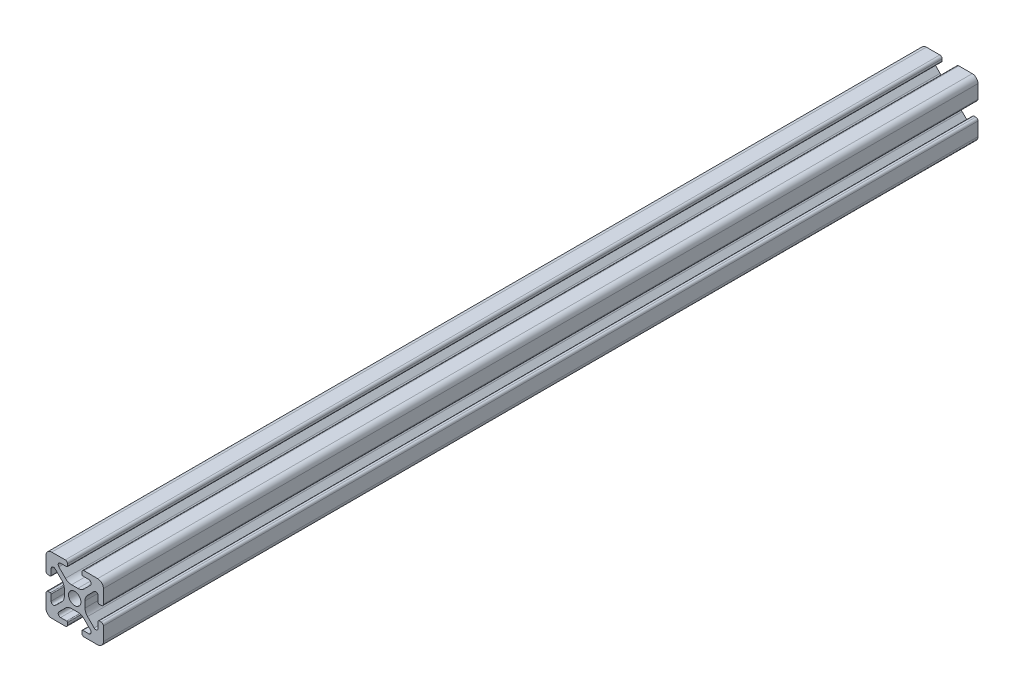
SolidWorks part; units mm, degrees
ref_plane "Front Plane" through (0, 0, 0) normal (0, 0, 1) x (1, 0, 0)
ref_plane "Top Plane" through (0, 0, 0) normal (0, 1, 0) x (1, 0, 0)
ref_plane "Right Plane" through (0, 0, 0) normal (1, 0, 0) x (0, 0, -1)
sketch "Sketch1" plane through (0, 0, 0) normal (0, 0, 1) x (1, 0, 0)
  line L0 (0, 10) -> (0, -10) construction
  line L1 (10, 0) -> (-10, 0) construction
  line L2 (-2.5, 10) -> (2.5, 10) construction
  line L3 (-5.75, 8.2) -> (5.75, 8.2) construction
  circle A0 centre (0, 0) radius 2.15 construction
  point P4 (0, 0)
  point P8 (0, 0)
  point P10 (0, 3.6)
  point P14 (0, 10)
  point P17 (0, 8.2)
  dimension "Thru Hole" = 4.3
  dimension "Height" = 20
  dimension "T Slot Depth" = 6.4
  dimension "T Slot Top Width" = 5
  dimension "T Slot Max Width" = 11.5
  dimension "Wall" = 1.8
sketch "Sketch2" plane through (0, 0, 0) normal (1, 0, 0) x (0, 0, -1)
  line L0 (152.4, 0) -> (-152.4, 0) construction
  point P4 (0, 0)
  dimension "D1" = 304.8
sketch "Sketch3" plane through (0, 0, 0) normal (0, 0, 1) x (1, 0, 0)
  line L0 (3.2874, 10) -> (8, 10)
  line L1 (10, 8) -> (10, -8) construction
  line L2 (8, -10) -> (-8, -10) construction
  line L3 (-10, 10) -> (10, -10) construction
  line L4 (2.5, 9.2126) -> (2.5, 8.5048)
  line L5 (-5.75, 8.2) -> (5.75, 8.2) construction
  line L6 (2.8048, 8.2) -> (4.9118, 8.2)
  line L7 (5.5045, 6.7691) -> (3.2141, 4.4787)
  line L8 (1.0928, 3.6) -> (-1.0928, 3.6)
  line L9 (0, 10) -> (0, -10) construction
  line L10 (5.75, 8.2) -> (5.75, 0) construction
  line L11 (10, 0) -> (-10, 0) construction
  line L12 (0, 0) -> (0, 10) construction
  line L13 (-2.5, 9.2126) -> (-2.5, 8.5048)
  line L14 (-5.5045, 6.7691) -> (-3.2141, 4.4787)
  line L15 (-2.8048, 8.2) -> (-4.9118, 8.2)
  line L16 (-3.2874, 10) -> (-8, 10)
  line L17 (0, 0) -> (-10, 0) construction
  line L18 (-10, 3.2874) -> (-10, 8)
  line L19 (-8.2, 2.8048) -> (-8.2, 4.9118)
  line L20 (-6.7691, 5.5045) -> (-4.4787, 3.2141)
  line L21 (-9.2126, 2.5) -> (-8.5048, 2.5)
  line L22 (-3.6, -1.0928) -> (-3.6, 1.0928)
  line L23 (-6.7691, -5.5045) -> (-4.4787, -3.2141)
  line L24 (-8.2, -2.8048) -> (-8.2, -4.9118)
  line L25 (-9.2126, -2.5) -> (-8.5048, -2.5)
  line L26 (-10, -3.2874) -> (-10, -8)
  line L27 (9.2126, -2.5) -> (8.5048, -2.5)
  line L28 (8.2, -2.8048) -> (8.2, -4.9118)
  line L29 (6.7691, -5.5045) -> (4.4787, -3.2141)
  line L30 (3.6, -1.0928) -> (3.6, 1.0928)
  line L31 (9.2126, 2.5) -> (8.5048, 2.5)
  line L32 (6.7691, 5.5045) -> (4.4787, 3.2141)
  line L33 (8.2, 2.8048) -> (8.2, 4.9118)
  line L34 (10, 8) -> (10, 3.2874)
  line L35 (10, -3.2874) -> (10, -8)
  line L36 (3.2874, -10) -> (8, -10)
  line L37 (-3.2874, -10) -> (-8, -10)
  line L38 (-6.7691, -5.5045) -> (-4.4787, -3.2141)
  line L39 (-2.8048, -8.2) -> (-4.9118, -8.2)
  line L40 (-5.5045, -6.7691) -> (-3.2141, -4.4787)
  line L41 (-2.5, -9.2126) -> (-2.5, -8.5048)
  line L42 (1.0928, -3.6) -> (-1.0928, -3.6)
  line L43 (5.5045, -6.7691) -> (3.2141, -4.4787)
  line L44 (2.8048, -8.2) -> (4.9118, -8.2)
  line L45 (2.5, -9.2126) -> (2.5, -8.5048)
  arc A0 (4.9118, 8.2) -> (5.5045, 6.7691) centre (4.9118, 7.3618) cw
  arc A1 (3.2141, 4.4787) -> (1.0928, 3.6) centre (1.0928, 6.6) cw
  circle A2 centre (0, 0) radius 2.15 construction
  circle A3 centre (0, 0) radius 2.15
  arc A4 (3.2874, 10) -> (2.5, 9.2126) centre (3.2874, 9.2126) ccw
  arc A5 (2.5, 8.5048) -> (2.8048, 8.2) centre (2.8048, 8.5048) ccw
  arc A6 (-3.2874, 10) -> (-2.5, 9.2126) centre (-3.2874, 9.2126) cw
  arc A7 (-4.9118, 8.2) -> (-5.5045, 6.7691) centre (-4.9118, 7.3618) ccw
  arc A8 (-3.2141, 4.4787) -> (-1.0928, 3.6) centre (-1.0928, 6.6) ccw
  arc A9 (-2.5, 8.5048) -> (-2.8048, 8.2) centre (-2.8048, 8.5048) cw
  arc A10 (-8.5048, 2.5) -> (-8.2, 2.8048) centre (-8.5048, 2.8048) ccw
  arc A11 (-4.4787, 3.2141) -> (-3.6, 1.0928) centre (-6.6, 1.0928) cw
  arc A12 (-8.2, 4.9118) -> (-6.7691, 5.5045) centre (-7.3618, 4.9118) cw
  arc A13 (-10, 3.2874) -> (-9.2126, 2.5) centre (-9.2126, 3.2874) ccw
  arc A14 (-8.5048, -2.5) -> (-8.2, -2.8048) centre (-8.5048, -2.8048) cw
  arc A15 (-10, -3.2874) -> (-9.2126, -2.5) centre (-9.2126, -3.2874) cw
  arc A16 (-4.4787, -3.2141) -> (-3.6, -1.0928) centre (-6.6, -1.0928) ccw
  arc A17 (-8.2, -4.9118) -> (-6.7691, -5.5045) centre (-7.3618, -4.9118) ccw
  arc A26 (-8, -10) -> (-10, -8) centre (-8, -8) cw
  arc A27 (-8, 10) -> (-10, 8) centre (-8, 8) ccw
  arc A28 (8, 10) -> (10, 8) centre (8, 8) cw
  arc A29 (10, -8) -> (8, -10) centre (8, -8) cw
  arc A30 (8.2, -4.9118) -> (6.7691, -5.5045) centre (7.3618, -4.9118) cw
  arc A31 (4.4787, -3.2141) -> (3.6, -1.0928) centre (6.6, -1.0928) cw
  arc A32 (10, -3.2874) -> (9.2126, -2.5) centre (9.2126, -3.2874) ccw
  arc A33 (8.5048, -2.5) -> (8.2, -2.8048) centre (8.5048, -2.8048) ccw
  arc A34 (10, 3.2874) -> (9.2126, 2.5) centre (9.2126, 3.2874) cw
  arc A35 (8.2, 4.9118) -> (6.7691, 5.5045) centre (7.3618, 4.9118) ccw
  arc A36 (4.4787, 3.2141) -> (3.6, 1.0928) centre (6.6, 1.0928) ccw
  arc A37 (8.5048, 2.5) -> (8.2, 2.8048) centre (8.5048, 2.8048) cw
  arc A38 (-2.5, -8.5048) -> (-2.8048, -8.2) centre (-2.8048, -8.5048) ccw
  arc A39 (-3.2141, -4.4787) -> (-1.0928, -3.6) centre (-1.0928, -6.6) cw
  arc A40 (-4.9118, -8.2) -> (-5.5045, -6.7691) centre (-4.9118, -7.3618) cw
  arc A41 (-3.2874, -10) -> (-2.5, -9.2126) centre (-3.2874, -9.2126) ccw
  arc A42 (2.5, -8.5048) -> (2.8048, -8.2) centre (2.8048, -8.5048) cw
  arc A43 (3.2874, -10) -> (2.5, -9.2126) centre (3.2874, -9.2126) cw
  arc A44 (3.2141, -4.4787) -> (1.0928, -3.6) centre (1.0928, -6.6) ccw
  arc A45 (4.9118, -8.2) -> (5.5045, -6.7691) centre (4.9118, -7.3618) ccw
  point P36 (2.5, 10)
  point P39 (2.5, 8.2)
  point P49 (0, 3.6)
  point P77 (-3.6, 0)
  point P78 (-8.2, -2.5)
  point P79 (-10, -2.5)
  point P104 (-10, -10)
  point P110 (10, 10)
  point P114 (10, -2.5)
  point P115 (8.2, -2.5)
  point P116 (3.6, 0)
  point P141 (0, -3.6)
  dimension "D1" = 3
  dimension "D2" = 0.8382
  dimension "D4" = 0.7874
  dimension "D5" = 0.3048
  dimension "D6" = 2
  dimension "D3" = 45
extrude "Boss-Extrude1" add sketch "Sketch3" along normal up to vertex (152.4 mm away) and the other way up to vertex (152.4 mm away) contours A45 L44 A42 L45 A43 L36 A29 L35 A32 L27 A33 L28 A30 L29 A31 L30 A36 L32 A35 L33 A37 L31 A34 L34 A28 L0 A4 L4 A5 L6 A0 L7 A1 L8 A8 L14 A7 L15 A9 L13 A6 L16 A27 L18 A13 L21 A10 L19 A12 L20 A11 up to point (0, 0, 152.4) other way up to point (0, 0, -152.4)
